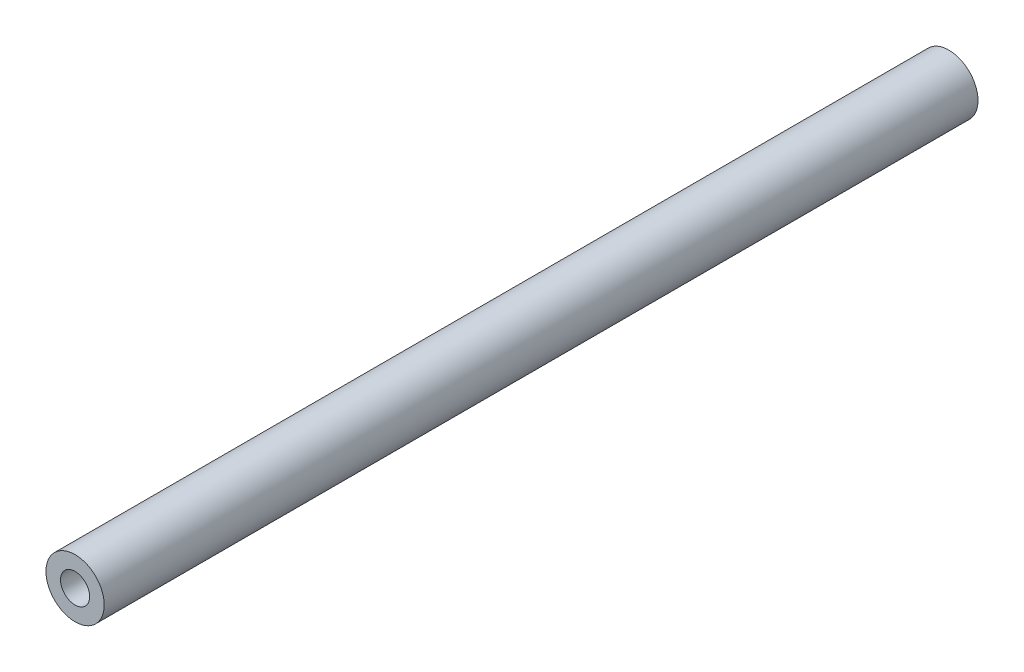
SolidWorks part; units mm, degrees
ref_plane "정면" through (0, 0, 0) normal (0, 0, 1) x (1, 0, 0)
ref_plane "윗면" through (0, 0, 0) normal (0, 1, 0) x (1, 0, 0)
ref_plane "우측면" through (0, 0, 0) normal (1, 0, 0) x (0, 0, -1)
sketch "스케치4" plane through (0, 0, 0) normal (0, 0, 1) x (1, 0, 0)
  circle A0 centre (0, 0) radius 2
  circle A1 centre (0, 0) radius 1
  dimension "D1" = 2
  dimension "D2" = 4
extrude "보스-돌출1" add sketch "스케치4" along normal blind 60
